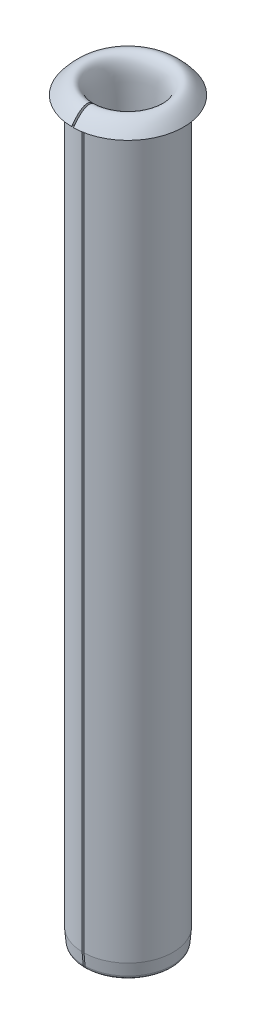
SolidWorks part; units mm, degrees
ref_plane "Front Plane" through (0, 0, 0) normal (0, 0, 1) x (1, 0, 0)
ref_plane "Top Plane" through (0, 0, 0) normal (0, 1, 0) x (1, 0, 0)
ref_plane "Right Plane" through (0, 0, 0) normal (1, 0, 0) x (0, 0, -1)
sketch "Sketch3" plane through (0, 0, 0) normal (1, 0, 0) x (0, 0, -1)
  line L0 (0, 25.2095) -> (0, -25.2095) construction
  line L1 (-1.8415, 0) -> (1.8415, 0) construction
  line L2 (-1.8415, 25.2095) -> (1.8415, 25.2095) construction
  line L3 (-1.8415, 25.2095) -> (-1.8415, -25.2095) construction
  line L4 (-1.8415, -25.2095) -> (1.8415, -25.2095) construction
  line L5 (1.8415, 25.2095) -> (1.8415, -25.2095) construction
  line L6 (-17.455, -9.0805) -> (15.8062, -9.0805) construction
  line L7 (1.9431, -9.0805) -> (1.9431, 6.0456)
  line L8 (1.9431, -9.0805) -> (2.9506, -9.0805) construction
  line L9 (2.9506, -9.0805) -> (2.9506, 24.2117)
  line L10 (2.9506, 24.2117) -> (2.9506, 24.9555)
  line L11 (3.2046, 25.2095) -> (3.6512, 25.2095)
  line L12 (1.9431, -9.0805) -> (1.9431, -23.0505)
  line L13 (1.9431, -23.0505) -> (2.9506, -23.0505)
  line L14 (2.9506, -23.0505) -> (2.9506, -9.0805)
  arc A0 (2.9506, 24.9555) -> (3.2046, 25.2095) centre (3.2046, 24.9555) cw
  spline S0 degree 3 poles (1.9431, 6.0456) (1.9431, 10.0918) (1.8911, 23.1641) (1.9557, 25.8913) (2.6573, 26.5305) (3.6513, 25.2095) knots 0 0 0 0 0.515432 0.615432 1 1 1 1
  point P7 (0, 25.2095)
  dimension "D7" = 0.254
  dimension "D1" = 3.683
  dimension "D2" = 50.419
  dimension "D3" = 34.29
  dimension "D4" = 0.1016
  dimension "D5" = 3.6512
  dimension "D6" = 1.016
  dimension "D8" = 1.0075
  dimension "D9" = 48.26
revolve "Revolve1" add sketch "Sketch3" angle 360 about L0
sketch "Sketch4" plane through (0, 0, 0) normal (0, 1, 0) x (1, 0, 0)
  line L1 (-0.0635, 0) -> (0.0635, 0)
  line L2 (-0.0635, 0) -> (-0.0635, -4.4455)
  line L3 (-0.0635, -4.4455) -> (0.0635, -4.4455)
  line L4 (0.0635, 0) -> (0.0635, -4.4455)
  dimension "D1" = 0.127
extrude "Cut-Extrude1" cut sketch "Sketch4" against normal through all both and the other way through all
chamfer "Chamfer1" distance 1.016 angle 5 1 edges at (0, -23.0505, -2.9506)
fillet "Fillet1" radius 0.254 1 edges at (0, -23.0505, -2.8617)
sketch "Sketch6" plane through (0, 0, 0) normal (1, 0, 0) x (0, 0, -1)
  line L0 (-3.6507, 25.2095) -> (3.6513, 25.2095) construction
  point P0 (0.0003, 25.2095)
